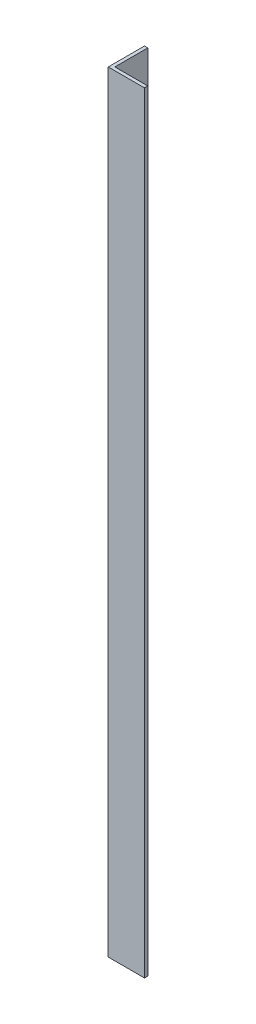
SolidWorks part; units mm, degrees
ref_plane "Спереди" through (0, 0, 0) normal (0, 0, 1) x (1, 0, 0)
ref_plane "Сверху" through (0, 0, 0) normal (0, 1, 0) x (1, 0, 0)
ref_plane "Справа" through (0, 0, 0) normal (1, 0, 0) x (0, 0, -1)
sketch "Эскиз1" plane through (0, 0, 0) normal (0, 1, 0) x (1, 0, 0)
  line L0 (0, -1.0719) -> (0, -21.0719)
  line L1 (0, -21.0719) -> (20, -21.0719)
  line L2 (20, -21.0719) -> (20, -23.0719)
  line L3 (20, -23.0719) -> (-2, -23.0719)
  line L4 (-2, -23.0719) -> (-2, -1.0719)
  line L5 (-2, -1.0719) -> (0, -1.0719)
extrude "Вытянуть1" add sketch "Эскиз1" along normal blind 468 from offset 40
